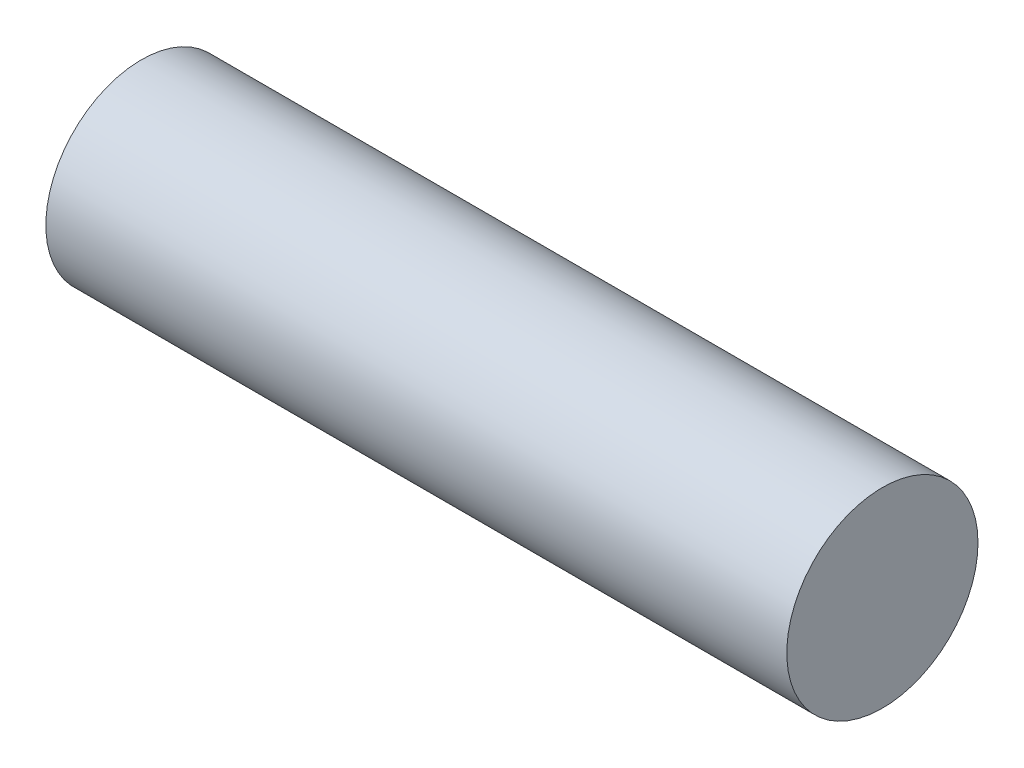
SolidWorks part; units mm, degrees
material "Stainless Steel (ferritic)"
ref_plane "Front Plane" through (0, 0, 0) normal (0, 0, 1) x (1, 0, 0)
ref_plane "Top Plane" through (0, 0, 0) normal (0, 1, 0) x (1, 0, 0)
ref_plane "Right Plane" through (0, 0, 0) normal (1, 0, 0) x (0, 0, -1)
sketch "Sketch2" plane through (0, 0, 0) normal (1, 0, 0) x (0, 0, -1)
  circle A0 centre (0, 0) radius 2
  dimension "D1" = 4
extrude "Boss-Extrude1" add sketch "Sketch2" along normal blind 15.5
